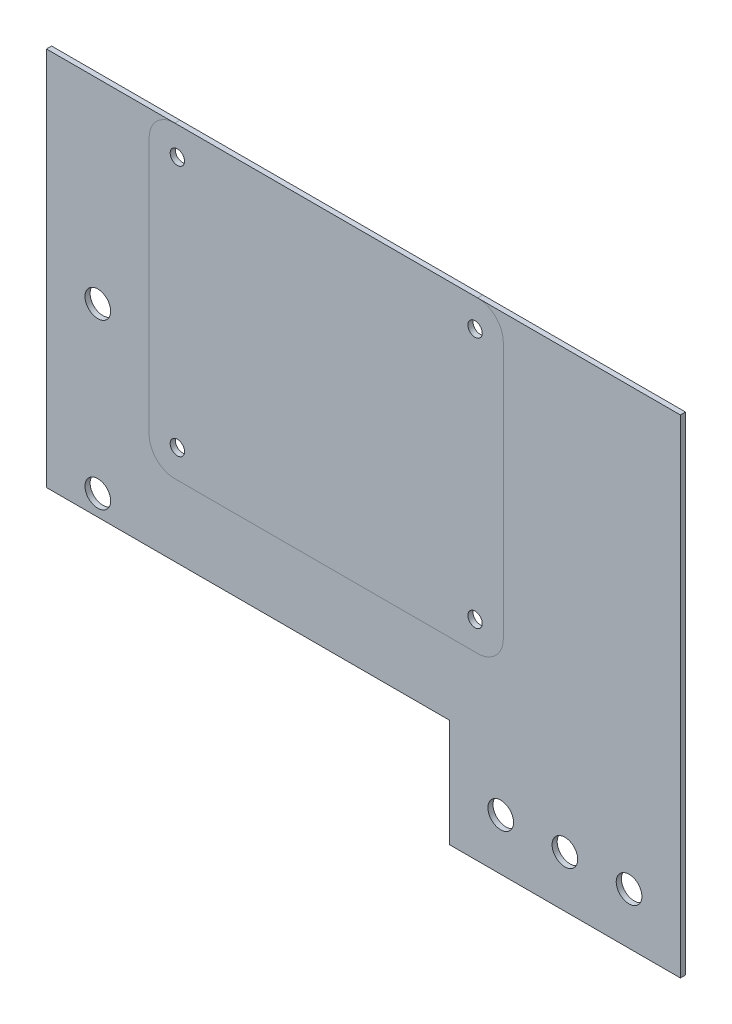
SolidWorks part; units mm, degrees
ref_plane "Front Plane" through (0, 0, 0) normal (0, 0, 1) x (1, 0, 0)
ref_plane "Top Plane" through (0, 0, 0) normal (0, 1, 0) x (1, 0, 0)
ref_plane "Right Plane" through (0, 0, 0) normal (1, 0, 0) x (0, 0, -1)
sketch3d "3DSketch1" plane through (0, 0, 0) normal (0, 0, 1) x (1, 0, 0)
sketch "Sketch3" plane through (0, 0, 55.2909) normal (0, 0, 1) x (1, 0, 0)
  line L20 (40.7272, 62.8578) -> (-18.2728, 62.8578)
  line L21 (-21.7728, 59.3578) -> (-21.7728, 9.3578)
  line L22 (-18.2728, 5.8578) -> (40.7272, 5.8578)
  line L23 (44.2272, 9.3578) -> (44.2272, 59.3578)
  line L24 (40.7272, 62.8578) -> (-18.2728, 62.8578)
  line L25 (-21.7728, 59.3578) -> (-21.7728, 9.3578)
  line L26 (-18.2728, 5.8578) -> (40.7272, 5.8578)
  line L27 (44.2272, 9.3578) -> (44.2272, 59.3578)
  line L44 (-23.2728, 59.3578) -> (-23.2728, 9.3578)
  line L45 (-18.2728, 4.3578) -> (40.7272, 4.3578)
  line L46 (45.7272, 9.3578) -> (45.7272, 59.3578)
  line L47 (40.7272, 64.3578) -> (-18.2728, 64.3578)
  line L48 (-23.2728, 59.3578) -> (-23.2728, 9.3578)
  line L49 (-18.2728, 4.3578) -> (40.7272, 4.3578)
  line L50 (45.7272, 9.3578) -> (45.7272, 59.3578)
  line L51 (40.7272, 64.3578) -> (-18.2728, 64.3578)
  arc A25 (-18.2728, 62.8578) -> (-21.7728, 59.3578) centre (-18.2728, 59.3578) ccw
  arc A26 (-21.7728, 9.3578) -> (-18.2728, 5.8578) centre (-18.2728, 9.3578) ccw
  arc A27 (40.7272, 5.8578) -> (44.2272, 9.3578) centre (40.7272, 9.3578) ccw
  arc A28 (44.2272, 59.3578) -> (40.7272, 62.8578) centre (40.7272, 59.3578) ccw
  arc A29 (-18.2728, 62.8578) -> (-21.7728, 59.3578) centre (-18.2728, 59.3578) ccw
  arc A30 (-21.7728, 9.3578) -> (-18.2728, 5.8578) centre (-18.2728, 9.3578) ccw
  arc A31 (40.7272, 5.8578) -> (44.2272, 9.3578) centre (40.7272, 9.3578) ccw
  arc A32 (44.2272, 59.3578) -> (40.7272, 62.8578) centre (40.7272, 59.3578) ccw
  arc A53 (-23.2728, 9.3578) -> (-18.2728, 4.3578) centre (-18.2728, 9.3578) ccw
  arc A54 (40.7272, 4.3578) -> (45.7272, 9.3578) centre (40.7272, 9.3578) ccw
  arc A55 (45.7272, 59.3578) -> (40.7272, 64.3578) centre (40.7272, 59.3578) ccw
  arc A56 (-18.2728, 64.3578) -> (-23.2728, 59.3578) centre (-18.2728, 59.3578) ccw
  arc A57 (-23.2728, 9.3578) -> (-18.2728, 4.3578) centre (-18.2728, 9.3578) ccw
  arc A58 (40.7272, 4.3578) -> (45.7272, 9.3578) centre (40.7272, 9.3578) ccw
  arc A59 (45.7272, 59.3578) -> (40.7272, 64.3578) centre (40.7272, 59.3578) ccw
  arc A60 (-18.2728, 64.3578) -> (-23.2728, 59.3578) centre (-18.2728, 59.3578) ccw
  dimension "D1" = 0.5
  dimension "D2" = 2
extrude "Boss-Extrude1" add sketch "Sketch3" along normal blind 6.5 and the other way blind 1
sketch "Sketch5" plane through (0, 0, 55.2909) normal (0, 0, 1) x (1, 0, 0)
  line L0 (44.2272, 34.3578) -> (-21.7728, 34.3578) construction
  line L1 (44.2272, 9.3578) -> (44.2272, 59.3578) construction
  line L2 (-21.7728, 59.3578) -> (-21.7728, 9.3578) construction
  line L3 (11.2272, 62.8578) -> (11.2272, 5.8578) construction
  line L4 (40.7272, 62.8578) -> (-18.2728, 62.8578) construction
  line L5 (-18.2728, 5.8578) -> (40.7272, 5.8578) construction
  circle A0 centre (-17.7728, 58.8578) radius 3
  circle A1 centre (40.2272, 58.8578) radius 3
  circle A2 centre (-17.7728, 9.8578) radius 3
  circle A3 centre (40.2272, 9.8578) radius 3
  circle A4 centre (-17.7728, 9.8578) radius 1.4
  circle A5 centre (-17.7728, 58.8578) radius 1.4
  circle A6 centre (40.2272, 58.8578) radius 1.4
  circle A7 centre (40.2272, 9.8578) radius 1.4
sketch "Sketch6" plane through (0, 4.3578, 0) normal (0, -1, 0) x (1, 0, 0)
  line L0 (40.7272, 58.0409) -> (28.2272, 58.0409) construction
  line L1 (40.7272, 61.7909) -> (40.7272, 54.2909) construction
  line L2 (28.2272, 61.7909) -> (28.2272, 59.5909)
  line L3 (-18.2728, 61.7909) -> (40.7272, 61.7909) construction
  line L4 (28.2272, 59.5909) -> (36.2272, 59.5909)
  line L5 (40.7272, 61.5285) -> (32.2272, 61.5285) construction
  line L6 (36.2272, 59.5909) -> (36.2272, 61.7909)
  line L7 (36.2272, 61.7909) -> (28.2272, 61.7909)
sketch "Sketch7" plane through (0, 4.3578, 0) normal (0, -1, 0) x (1, 0, 0)
  line L0 (-18.2728, 58.0409) -> (18.7272, 58.0409) construction
  line L1 (-18.2728, 61.7909) -> (-18.2728, 54.2909) construction
  line L7 (18.7272, 61.7909) -> (18.7272, 59.7909)
  line L8 (18.7272, 59.7909) -> (2.7272, 59.7909)
  line L9 (2.7272, 59.7909) -> (2.7272, 61.7909)
  line L10 (-18.2728, 61.7909) -> (40.7272, 61.7909) construction
  line L11 (2.7272, 61.7909) -> (18.7272, 61.7909)
sketch "Sketch8" plane through (0, 4.3578, 0) normal (0, -1, 0) x (1, 0, 0)
  line L0 (-18.2728, 58.0409) -> (-6.1728, 58.0409) construction
  line L1 (-18.2728, 61.7909) -> (-18.2728, 54.2909) construction
  line L7 (-6.1728, 61.7909) -> (-6.1728, 58.9909)
  line L8 (-18.2728, 61.7909) -> (40.7272, 61.7909) construction
  line L9 (-6.1728, 58.9909) -> (-15.1728, 58.9909)
  line L10 (-15.1728, 58.9909) -> (-15.1728, 61.7909)
  line L11 (-15.1728, 61.7909) -> (-6.1728, 61.7909)
sketch "Sketch9" plane through (45.7272, 0, 0) normal (1, 0, 0) x (0, 0, -1)
  line L0 (-58.0409, 9.3578) -> (-58.0409, 45.8078) construction
  line L1 (-61.7909, 9.3578) -> (-54.2909, 9.3578) construction
  line L3 (-59.7909, 45.3078) -> (-59.7909, 29.8078)
  line L9 (-59.7909, 29.8078) -> (-61.7909, 29.8078)
  line L10 (-61.7909, 9.3578) -> (-61.7909, 59.3578) construction
  line L12 (-61.7909, 45.3078) -> (-59.7909, 45.3078)
  line L13 (-61.7909, 45.3078) -> (-61.7909, 29.8078)
sketch "Sketch10" plane through (-23.2728, 0, 0) normal (-1, 0, 0) x (0, 0, 1)
  line L0 (58.0409, 9.3578) -> (58.0409, 42.6578) construction
  line L1 (61.7909, 9.3578) -> (54.2909, 9.3578) construction
  line L2 (54.2909, 42.6578) -> (59.2909, 42.6578)
  line L3 (54.2909, 59.3578) -> (54.2909, 9.3578) construction
  line L4 (59.2909, 42.6578) -> (59.2909, 26.6578)
  line L5 (59.2909, 26.6578) -> (54.2909, 26.6578)
  line L6 (54.2909, 26.6578) -> (54.2909, 42.6578)
sketch "Sketch11" plane through (0, 0, 55.2909) normal (0, 0, 1) x (1, 0, 0)
  line L25 (-23.2728, 26.6578) -> (-23.2728, 42.6578)
  line L30 (-23.2728, 26.6578) -> (-23.2728, 9.3578)
  line L31 (-18.2728, 4.3578) -> (40.7272, 4.3578)
  line L32 (-23.2728, 59.3578) -> (-23.2728, 42.6578)
  line L33 (40.7272, 64.3578) -> (-18.2728, 64.3578)
  line L34 (45.7272, 9.3578) -> (45.7272, 59.3578)
  line L35 (-23.2728, 26.6578) -> (-23.2728, 9.3578)
  line L36 (-18.2728, 4.3578) -> (40.7272, 4.3578)
  line L37 (-23.2728, 59.3578) -> (-23.2728, 42.6578)
  line L38 (40.7272, 64.3578) -> (-18.2728, 64.3578)
  line L39 (45.7272, 9.3578) -> (45.7272, 59.3578)
  arc A31 (-23.2728, 9.3578) -> (-18.2728, 4.3578) centre (-18.2728, 9.3578) ccw
  arc A32 (-18.2728, 64.3578) -> (-23.2728, 59.3578) centre (-18.2728, 59.3578) ccw
  arc A33 (45.7272, 59.3578) -> (40.7272, 64.3578) centre (40.7272, 59.3578) ccw
  arc A34 (40.7272, 4.3578) -> (45.7272, 9.3578) centre (40.7272, 9.3578) ccw
  arc A35 (-23.2728, 9.3578) -> (-18.2728, 4.3578) centre (-18.2728, 9.3578) ccw
  arc A36 (-18.2728, 64.3578) -> (-23.2728, 59.3578) centre (-18.2728, 59.3578) ccw
  arc A37 (45.7272, 59.3578) -> (40.7272, 64.3578) centre (40.7272, 59.3578) ccw
  arc A38 (40.7272, 4.3578) -> (45.7272, 9.3578) centre (40.7272, 9.3578) ccw
  dimension "D1" = 0
extrude "Boss-Extrude5" add sketch "Sketch5" along normal blind 3.2 separate body
sketch "Sketch13" plane through (0, 0, 55.2909) normal (0, 0, 1) x (1, 0, 0)
  line L21 (-23.2728, 26.6578) -> (-23.2728, 42.6578)
  line L26 (-23.2728, 26.6578) -> (-23.2728, 9.3578)
  line L27 (-23.2728, 59.3578) -> (-23.2728, 42.6578)
  line L28 (40.7272, 64.3578) -> (-18.2728, 64.3578)
  line L29 (45.7272, 9.3578) -> (45.7272, 59.3578)
  line L30 (-18.2728, 4.3578) -> (40.7272, 4.3578)
  line L31 (-23.2728, 26.6578) -> (-23.2728, 9.3578)
  line L32 (-23.2728, 59.3578) -> (-23.2728, 42.6578)
  line L33 (40.7272, 64.3578) -> (-18.2728, 64.3578)
  line L34 (45.7272, 9.3578) -> (45.7272, 59.3578)
  line L35 (-18.2728, 4.3578) -> (40.7272, 4.3578)
  arc A28 (-18.2728, 64.3578) -> (-23.2728, 59.3578) centre (-18.2728, 59.3578) ccw
  arc A29 (45.7272, 59.3578) -> (40.7272, 64.3578) centre (40.7272, 59.3578) ccw
  arc A30 (40.7272, 4.3578) -> (45.7272, 9.3578) centre (40.7272, 9.3578) ccw
  arc A31 (-23.2728, 9.3578) -> (-18.2728, 4.3578) centre (-18.2728, 9.3578) ccw
  arc A32 (-18.2728, 64.3578) -> (-23.2728, 59.3578) centre (-18.2728, 59.3578) ccw
  arc A33 (45.7272, 59.3578) -> (40.7272, 64.3578) centre (40.7272, 59.3578) ccw
  arc A34 (40.7272, 4.3578) -> (45.7272, 9.3578) centre (40.7272, 9.3578) ccw
  arc A35 (-23.2728, 9.3578) -> (-18.2728, 4.3578) centre (-18.2728, 9.3578) ccw
  dimension "D1" = 0
extrude "Boss-Extrude6" add sketch "Sketch13" against normal blind 1.3
sketch "Sketch17" plane through (0, 0, 55.2909) normal (0, 0, 1) x (1, 0, 0)
  line L0 (44.2272, 34.3578) -> (-21.9476, 34.3578) construction
  line L1 (44.2272, 9.3578) -> (44.2272, 59.3578) construction
  line L2 (11.2272, 5.8578) -> (11.2272, 62.8578) construction
  line L3 (-18.2728, 5.8578) -> (40.7272, 5.8578) construction
  line L4 (40.7272, 62.8578) -> (-18.2728, 62.8578) construction
  circle A0 centre (40.2272, 9.8578) radius 1.4
  circle A1 centre (-17.7728, 9.8578) radius 1.4
  circle A2 centre (-17.7728, 58.8578) radius 1.4
  circle A3 centre (40.2272, 58.8578) radius 1.4
extrude "Cut-Extrude9" cut sketch "Sketch17" against normal blind 1.5
sketch "Sketch18" plane through (0, 0, 58.4909) normal (0, 0, 1) x (1, 0, 0)
  line L1 (67.9798, -11.5209) -> (-50.5034, -11.5209)
  line L2 (67.9798, -11.5209) -> (67.9798, 101.5715)
  line L3 (67.9798, 101.5715) -> (-50.5034, 101.5715)
  line L4 (-50.5034, -11.5209) -> (-50.5034, 101.5715)
extrude "Cut-Extrude10" cut sketch "Sketch18" against normal blind 3.5 and the other way blind 10
sketch "Sketch23" plane through (0, 0, 54.9909) normal (0, 0, 1) x (1, 0, 0)
  line L1 (-43.0293, 64.3578) -> (56.9707, 64.3578)
  line L2 (-43.0293, 64.3578) -> (-43.0293, -5.6422)
  line L3 (-43.0293, -5.6422) -> (56.9707, -5.6422)
  line L4 (56.9707, 64.3578) -> (56.9707, -5.6422)
  line L6 (45.2272, -20.6422) -> (57.7272, -20.6422)
  line L7 (57.7272, -20.6422) -> (70.2272, -20.6422)
  line L8 (-23.2728, 59.3578) -> (-23.2728, 9.3578) construction
  line L9 (-43.0293, -5.6422) -> (-43.0293, 58.3578)
  line L10 (118.6414, -20.6422) -> (118.6414, 73.3578)
  line L11 (-33.2728, 78.7114) -> (148.7272, 78.7114)
  line L12 (40.7272, 64.3578) -> (-18.2728, 64.3578) construction
  line L13 (-43.2728, 64.3578) -> (80.2272, 64.3578)
  line L14 (-43.2728, 64.3578) -> (-43.2728, -30.6422)
  line L15 (-43.2728, -30.6422) -> (80.2272, -30.6422)
  line L16 (80.2272, 64.3578) -> (80.2272, -30.6422)
  line L17 (-43.2728, -30.6422) -> (35.2272, -30.6422)
  line L18 (-43.2728, -30.6422) -> (-43.2728, -9.6422)
  line L19 (-43.2728, -9.6422) -> (35.2272, -9.6422)
  line L20 (35.2272, -30.6422) -> (35.2272, -9.6422)
  line L21 (80.2272, 64.3578) -> (56.9707, 64.3578)
  line L22 (80.2272, 64.3578) -> (80.2272, -5.6422)
  line L23 (80.2272, -5.6422) -> (56.9707, -5.6422)
  line L24 (56.9707, 64.3578) -> (56.9707, -5.6422)
  circle A1 centre (45.2272, -20.6422) radius 2.5
  circle A2 centre (57.7272, -20.6422) radius 2.5
  circle A3 centre (70.2272, -20.6422) radius 2.5
  circle A4 centre (-33.2728, -5.6422) radius 2.5
  circle A5 centre (-33.2728, 26.3578) radius 2.5
  point P6 (57.7272, 78.7114)
  point P20 (-43.0293, 26.3578)
  point P24 (118.6414, 26.3578)
  dimension "D3" = 5
  dimension "D1" = 70
  dimension "D2" = 100
  dimension "D4" = 25
  dimension "D5" = 32
  dimension "D6" = 182
  dimension "D7" = 64
  dimension "D8" = 94
  dimension "D9" = 10
  dimension "D10" = 10
  dimension "D11" = 10
  dimension "D12" = 10
  dimension "D13" = 10
  dimension "D14" = 4
extrude "Boss-Extrude7" add sketch "Sketch23" against normal blind 1 separate body
sketch "Sketch25" plane through (0, 0, 54.9909) normal (0, 0, 1) x (1, 0, 0)
  line L0 (-17.7728, 58.8578) -> (40.2272, 58.8578)
  line L1 (-17.7728, 58.8578) -> (-17.7728, 9.8578)
  line L2 (40.2272, 58.8578) -> (40.2272, 9.8578)
  line L3 (-17.7728, 9.8578) -> (40.2272, 9.8578)
  circle A0 centre (-17.7728, 9.8578) radius 1.4 construction
  circle A1 centre (-17.7728, 58.8578) radius 1.4
